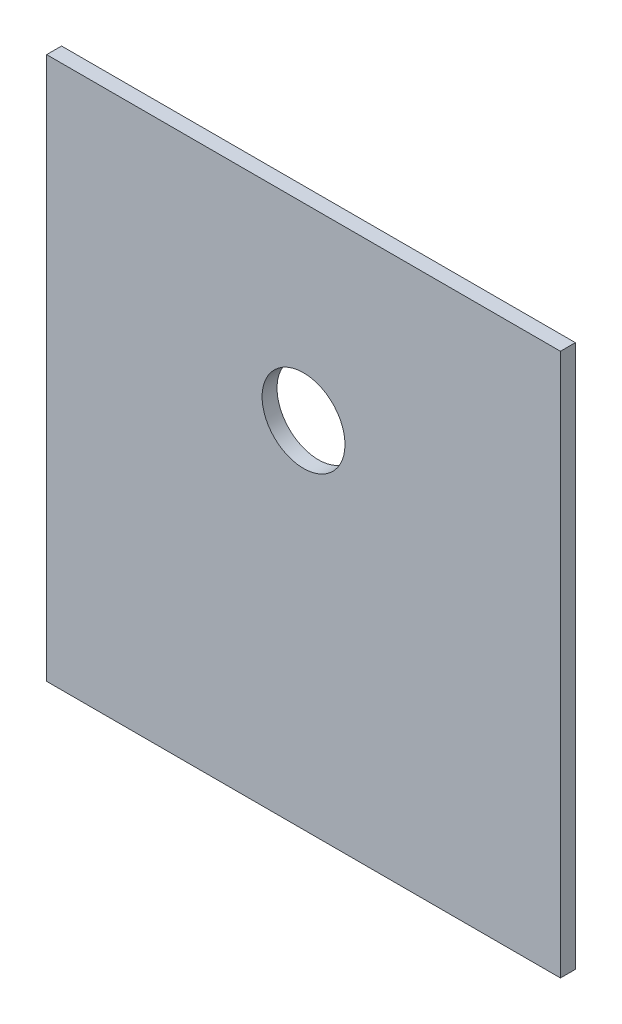
SolidWorks part; units mm, degrees
ref_plane "Front Plane" through (0, 0, 0) normal (0, 0, 1) x (1, 0, 0)
ref_plane "Top Plane" through (0, 0, 0) normal (0, 1, 0) x (1, 0, 0)
ref_plane "Right Plane" through (0, 0, 0) normal (1, 0, 0) x (0, 0, -1)
sketch "Sketch1" plane through (0, 0, 0) normal (0, 0, 1) x (1, 0, 0)
  line L1 (-31, -32.75) -> (31, -32.75)
  line L2 (-31, -32.75) -> (-31, 32.75)
  line L3 (-31, 32.75) -> (31, 32.75)
  line L4 (31, -32.75) -> (31, 32.75)
  line L5 (-31, -32.75) -> (31, 32.75) construction
  line L6 (-31, 32.75) -> (31, -32.75) construction
  point P0 (0, 0)
  dimension "D1" = 65.5
  dimension "D2" = 62
extrude "Boss-Extrude1" add sketch "Sketch1" along normal mid plane 1.8
sketch "Sketch2" plane through (0, 0, 0.9) normal (0, 0, 1) x (1, 0, 0)
  circle A0 centre (0, 10) radius 5
  point P2 (1.7785, 11.1391)
  point P7 (0, 5.7097)
  dimension "D1" = 10
  dimension "D2" = 10
extrude "Cut-Extrude1" cut sketch "Sketch2" against normal through all
